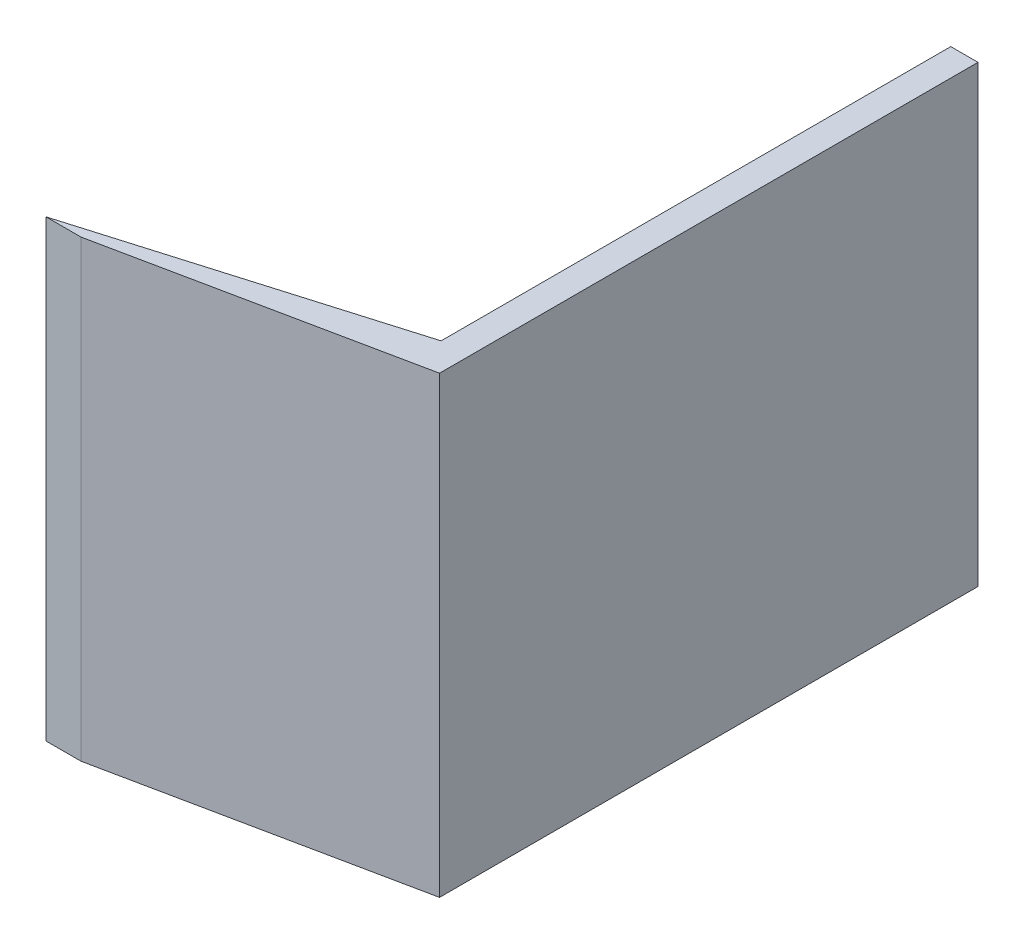
SolidWorks part; units mm, degrees
material "Perspex (TM) GS Acrylic Cast Sheet"
ref_plane "Front Plane" through (0, 0, 0) normal (0, 0, 1) x (1, 0, 0)
ref_plane "Top Plane" through (0, 0, 0) normal (0, 1, 0) x (1, 0, 0)
ref_plane "Right Plane" through (0, 0, 0) normal (1, 0, 0) x (0, 0, -1)
sketch "Sketch1" plane through (0, 0, 0) normal (0, 1, 0) x (1, 0, 0)
  line L0 (0, 46.72) -> (0, 0)
  line L2 (3, 0) -> (3, 46.72)
  line L3 (3, 46.72) -> (0, 46.72)
  line L4 (-8.1614, -11.8261) -> (-33.5868, -19.3412)
  line L5 (-29.7248, -19.3412) -> (-7.554, -14.764)
  line L6 (-33.5868, -19.3412) -> (-29.7248, -19.3412)
  line L7 (0.0002, -0.0334) -> (3, 0)
  line L8 (0, 0) -> (0.0002, -0.0334)
  line L9 (0.0002, -0.0334) -> (0.0002, -9.4138)
  line L10 (-8.1614, -11.8261) -> (0.0002, -9.4138)
  line L11 (-7.554, -14.764) -> (3, -12.5851)
  line L12 (3, 0) -> (3, -12.5851)
  spline S0 degree 1 poles (0.0002, -0.0334) (-8.1614, -11.8261) knots 0 0 1 1 construction
  spline S1 degree 2 poles (3, 0) (3.1399, -12.5531) (-7.554, -14.764) knots 0 0 0 1 1 1 construction
  spline S2 degree 3 poles (0.0002, -0.0334) (0.0052, -0.4868) (-0.0095, -1.4173) (-0.1374, -3.0879) (-0.4716, -4.9478) (-1.1168, -6.7822) (-1.9737, -8.2695) (-3.0429, -9.4773) (-4.3717, -10.472) (-5.7648, -11.143) (-7.0595, -11.5706) (-7.7988, -11.7512) (-8.1614, -11.8261) knots 0 0 0 0 0.0625 0.125 0.25 0.375 0.5 0.625 0.75 0.875 0.9375 1 1 1 1 construction
  point P9 (0, 0)
  point P13 (0, 0)
  dimension "D2" = 3
  dimension "D4" = 0.0002
  dimension "D5" = 1.6895
  dimension "D6" = 7.554
  dimension "D7" = 8.1614
  dimension "D8" = 29.7248
  dimension "D9" = 33.5868
  dimension "D10" = 19.3412
  dimension "D11" = 46.72
  dimension "D3" = 3
extrude "Boss-Extrude1" add sketch "Sketch1" along normal blind 50 contours L0 L8 L7 L2 L3 | L7 S2 L4 L6 L5 S1
